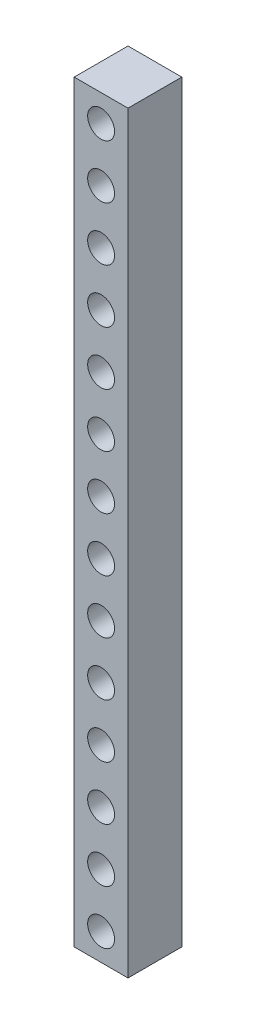
SolidWorks part; units mm, degrees
ref_plane "Plan de face" through (0, 0, 0) normal (0, 0, 1) x (1, 0, 0)
ref_plane "Plan de dessus" through (0, 0, 0) normal (0, 1, 0) x (1, 0, 0)
ref_plane "Plan de droite" through (0, 0, 0) normal (1, 0, 0) x (0, 0, -1)
sketch "Esquisse1" plane through (0, 0, 0) normal (0, 0, 1) x (1, 0, 0)
  line L0 (0, 70) -> (0, 92.8586) construction
  line L1 (5, 70) -> (-5, 70)
  line L2 (5, 70) -> (5, -70)
  line L3 (5, -70) -> (-5, -70)
  line L4 (-5, 70) -> (-5, -70)
  line L5 (5, 70) -> (-5, -70) construction
  line L6 (5, -70) -> (-5, 70) construction
  circle A0 centre (0, 65) radius 2.5
  circle A1 centre (0, 55) radius 2.5
  circle A2 centre (0, 45) radius 2.5
  circle A3 centre (0, 35) radius 2.5
  circle A4 centre (0, 25) radius 2.5
  circle A5 centre (0, 15) radius 2.5
  circle A6 centre (0, 5) radius 2.5
  circle A7 centre (0, -5) radius 2.5
  circle A8 centre (0, -15) radius 2.5
  circle A9 centre (0, -25) radius 2.5
  circle A10 centre (0, -35) radius 2.5
  circle A11 centre (0, -45) radius 2.5
  circle A12 centre (0, -55) radius 2.5
  circle A13 centre (0, -65) radius 2.5
  point P0 (0, 0)
  dimension "D4" = 5
  dimension "D1" = 140
  dimension "D2" = 10
  dimension "D3" = 5
  dimension "D5" = 14
extrude "BASE" add sketch "Esquisse1" along normal blind 10
